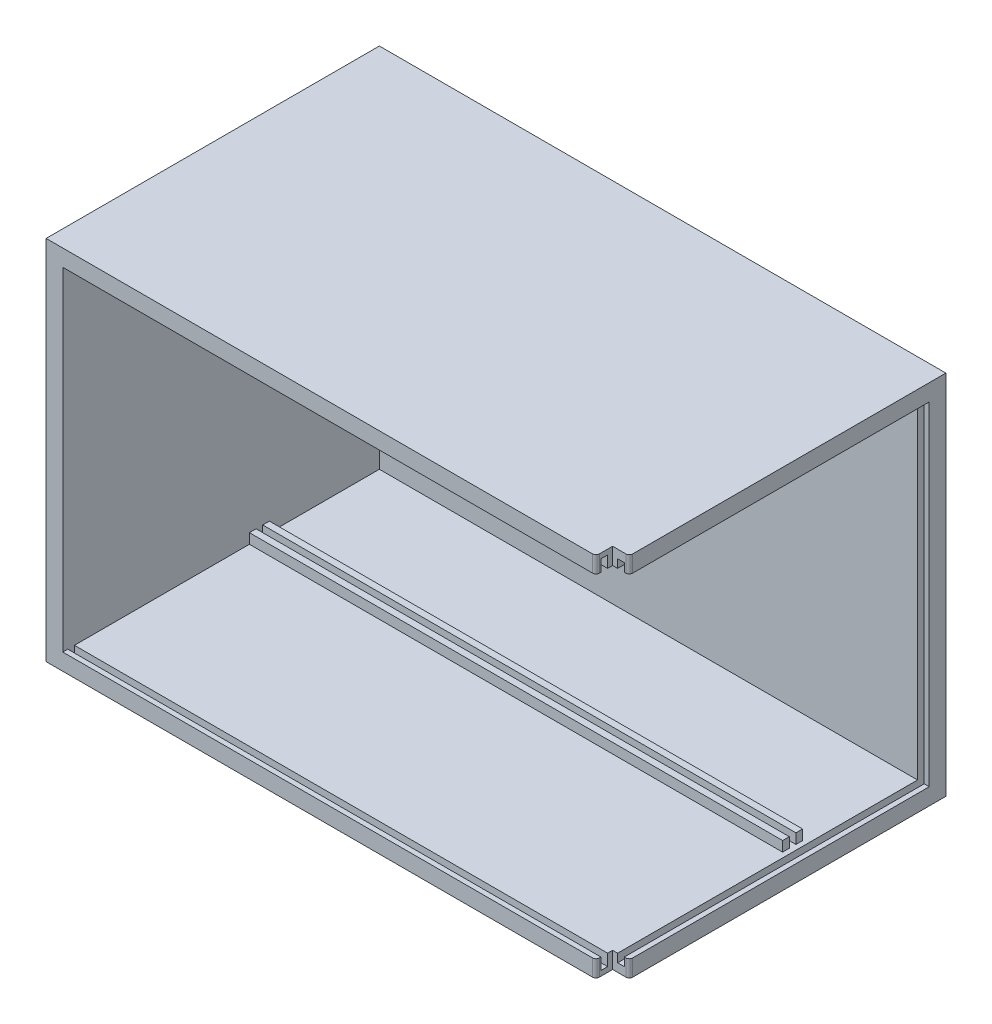
SolidWorks part; units mm, degrees
ref_plane "Front Plane" through (0, 0, 0) normal (0, 0, 1) x (1, 0, 0)
ref_plane "Top Plane" through (0, 0, 0) normal (0, 1, 0) x (1, 0, 0)
ref_plane "Right Plane" through (0, 0, 0) normal (1, 0, 0) x (0, 0, -1)
sketch "Sketch2" plane through (0, 0, 0) normal (0, 0, 1) x (1, 0, 0)
  line L0 (-80, 55) -> (80, 55)
  line L1 (-75, -50) -> (75, -50)
  line L2 (-75, -50) -> (-75, 50)
  line L3 (-75, 50) -> (75, 50)
  line L4 (75, -50) -> (75, 50)
  line L5 (-75, -50) -> (75, 50) construction
  line L6 (-75, 50) -> (75, -50) construction
  line L7 (80, -55) -> (80, 55)
  line L8 (-80, -55) -> (80, -55)
  line L9 (-80, -55) -> (-80, 55)
  line L10 (-80, -50) -> (-75, -50)
  line L11 (-80, 50) -> (-75, 50)
  line L12 (75, 50) -> (80, 50)
  line L13 (75, -50) -> (80, -50)
  point P0 (0, 0)
  dimension "D1" = 100
  dimension "D2" = 150
  dimension "D3" = 5
extrude "Boss-Extrude1" add sketch "Sketch2" along normal blind 90 contours L3 L12 L7 L0 L9 L11 | L13 L1 L10 L9 L8 L7
sketch "Sketch3" plane through (80, 0, 0) normal (1, 0, 0) x (0, 0, -1)
  line L0 (0, 50) -> (0, -54.3866) construction
  line L1 (-35, 50) -> (-35, 46.9737)
  line L2 (0, 0) -> (15.3624, 0) construction
  line L4 (-35, -50) -> (-35, -46.9737)
  line L5 (-39, 50) -> (-39, 46.9737)
  line L6 (-90, 50) -> (0, 50) construction
  line L7 (-39, -50) -> (-39, -46.9737)
  point P16 (-35, 48.4869)
  dimension "D1" = 35
  dimension "D2" = 4
extrude "Extrude-Thin1" add sketch "Sketch3" against normal blind 160 thin
sketch "Sketch5" plane through (0, 0, 0) normal (0, 0, -1) x (-1, 0, 0)
  line L1 (-80, -55) -> (80, -55)
  line L2 (-80, -55) -> (-80, 55)
  line L3 (-80, 55) -> (80, 55)
  line L4 (80, -55) -> (80, 55)
  line L5 (-80, -55) -> (80, 55) construction
  line L6 (-80, 55) -> (80, -55) construction
  point P0 (0, 0)
extrude "Boss-Extrude2" add sketch "Sketch5" along normal blind 5
sketch "Sketch6" plane through (80, 0, 0) normal (1, 0, 0) x (0, 0, -1)
  line L0 (-90, 55) -> (-90, 50)
  line L1 (-90, 50) -> (0, 50)
  line L2 (0, 50) -> (0, -50)
  line L3 (0, -50) -> (-90, -50)
  line L4 (-90, -50) -> (-90, -55)
  line L5 (-90, -55) -> (5, -55)
  line L6 (5, -55) -> (5, 55)
  line L7 (5, 55) -> (-90, 55)
extrude "Boss-Extrude3" add sketch "Sketch6" along normal blind 5
sketch "Sketch7" plane through (0, 0, 0) normal (0, 0, 1) x (1, 0, 0)
  line L0 (81.5, 50) -> (83.5, 50)
  line L1 (83.5, 50) -> (83.5, -50)
  line L2 (-80, 50) -> (85, 50) construction
  line L3 (-80, -50) -> (85, -50) construction
  line L4 (81.5, -50) -> (83.5, -50)
  line L5 (85, 50) -> (85, -50) construction
  line L6 (81.5, 50) -> (81.5, -50)
  line L7 (-80, 50) -> (85, 50) construction
  line L8 (-80, -50) -> (85, -50) construction
  dimension "D2" = 1.5
extrude "Cut-Extrude1" cut sketch "Sketch7" against normal blind 2.5
sketch "Sketch8" plane through (0, 50, 0) normal (0, -1, 0) x (1, 0, 0)
  line L0 (81.5, 0) -> (81.5, 90)
  line L1 (-80, 90) -> (85, 90) construction
  line L2 (83.5, 0) -> (83.5, 90)
  line L3 (81.5, 0) -> (83.5, 0)
  line L4 (81.5, 90) -> (83.5, 90)
extrude "Cut-Extrude2" cut sketch "Sketch8" against normal blind 2.5
sketch "Sketch9" plane through (0, -50, 0) normal (0, 1, 0) x (1, 0, 0)
  line L0 (83.5, 0) -> (83.5, -90)
  line L1 (-80, -90) -> (85, -90) construction
  line L2 (81.5, 0) -> (81.5, -90)
  line L3 (81.5, 0) -> (83.5, 0)
  line L4 (81.5, -90) -> (83.5, -90)
extrude "Cut-Extrude3" cut sketch "Sketch9" against normal blind 2.5
sketch "Sketch10" plane through (0, 0, 0) normal (0, 0, 1) x (1, 0, 0)
  line L1 (81.5, 52.5) -> (83.5, 52.5)
  line L2 (81.5, 52.5) -> (81.5, 50)
  line L3 (81.5, 50) -> (83.5, 50)
  line L4 (83.5, 52.5) -> (83.5, 50)
  line L5 (81.5, -50) -> (83.5, -50)
  line L6 (81.5, -50) -> (81.5, -52.5)
  line L7 (81.5, -52.5) -> (83.5, -52.5)
  line L8 (83.5, -50) -> (83.5, -52.5)
extrude "Cut-Extrude4" cut sketch "Sketch10" against normal blind 2.5
sketch "Sketch11" plane through (-80, 0, 0) normal (-1, 0, 0) x (0, 0, 1)
  line L0 (90, 50) -> (90, 55)
  line L1 (90, 55) -> (95, 55)
  line L2 (95, 55) -> (95, 50)
  line L3 (91.5, 50) -> (91.5, 53.5)
  line L4 (91.5, 53.5) -> (93.5, 53.5)
  line L5 (93.5, 53.5) -> (93.5, 50)
  line L6 (95, 50) -> (93.5, 50)
  line L7 (91.5, 50) -> (90, 50)
  line L8 (52.25, 0) -> (-52.25, 0) construction
  line L9 (91.5, -53.5) -> (93.5, -53.5)
  line L10 (91.5, -50) -> (91.5, -53.5)
  line L11 (91.5, -50) -> (90, -50)
  line L12 (90, -50) -> (90, -55)
  line L13 (90, -55) -> (95, -55)
  line L14 (95, -55) -> (95, -50)
  line L15 (93.5, -53.5) -> (93.5, -50)
  line L16 (95, -50) -> (93.5, -50)
  dimension "D1" = 5
  dimension "D3" = 107
  dimension "D2" = 1.5
extrude "Boss-Extrude4" add sketch "Sketch11" against normal blind 160
sketch "Sketch12" plane through (-80, 0, 0) normal (-1, 0, 0) x (0, 0, 1)
  line L1 (-5, 55) -> (95, 55)
  line L2 (-5, 55) -> (-5, -55)
  line L3 (-5, -55) -> (95, -55)
  line L4 (95, 55) -> (95, -55)
extrude "Boss-Extrude5" add sketch "Sketch12" along normal blind 5
fillet "Fillet1" radius 1 4 edges at (80, -52.5, 95) (80, 52.5, 95) (85, 52.5, 90) (85, -52.5, 90)
sketch "Sketch14" plane through (-80, 0, 0) normal (1, 0, 0) x (0, 0, -1)
  point P0 (-64.5982, -2.4756)
